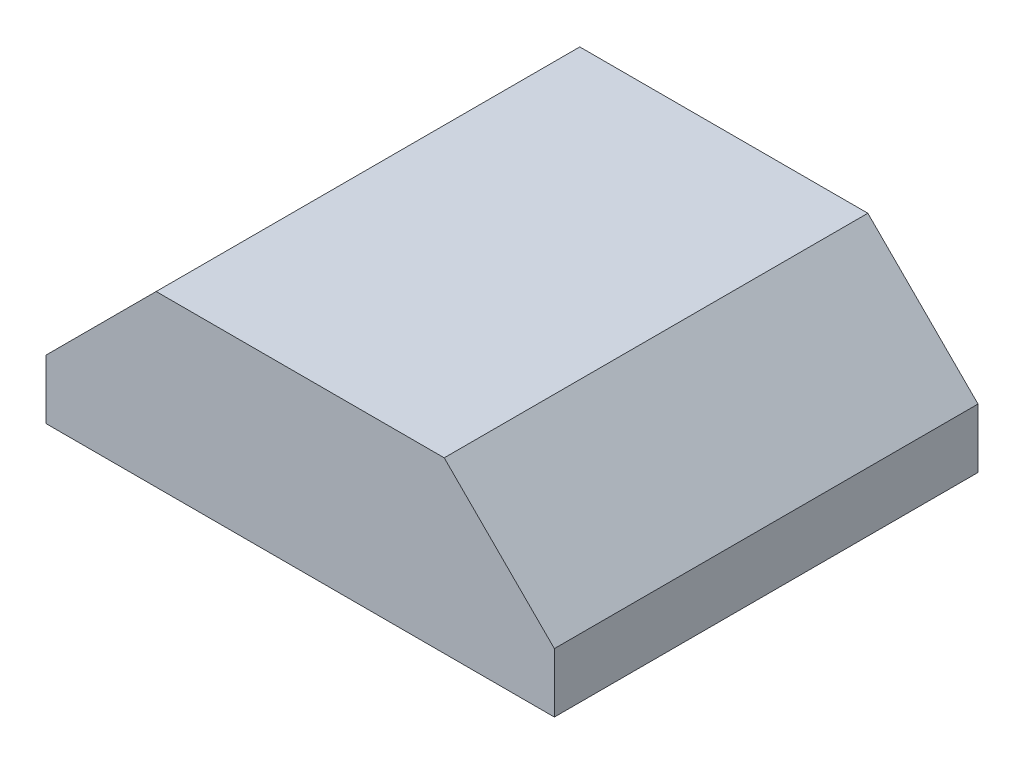
SolidWorks part; units mm, degrees
ref_plane "Ebene vorne" through (0, 0, 0) normal (0, 0, 1) x (1, 0, 0)
ref_plane "Ebene oben" through (0, 0, 0) normal (0, 1, 0) x (1, 0, 0)
ref_plane "Ebene rechts" through (0, 0, 0) normal (1, 0, 0) x (0, 0, -1)
sketch "Skizze1" plane through (0, 0, 0) normal (0, 0, 1) x (1, 0, 0)
  line L0 (0, 0) -> (0, 23680.6173) construction
  line L1 (3.4, 1.8089) -> (-3.4, 1.8089)
  line L2 (-3.4, 1.8089) -> (-6, -0.7911)
  line L3 (-6, -0.7911) -> (-6, -2.1911)
  line L4 (-6, -2.1911) -> (6, -2.1911)
  line L5 (6, -0.7911) -> (6, -2.1911)
  line L6 (3.4, 1.8089) -> (6, -0.7911)
  point P9 (0, -2.1911)
  point P11 (0, 1.8089)
  dimension "D1" = 3.4
  dimension "D2" = 6
  dimension "D3" = 4
  dimension "D4" = 135
extrude "Aufsatz-Linear austragen1" add sketch "Skizze1" along normal blind 10 contours L1 L2 L3 L4 L5 L6
